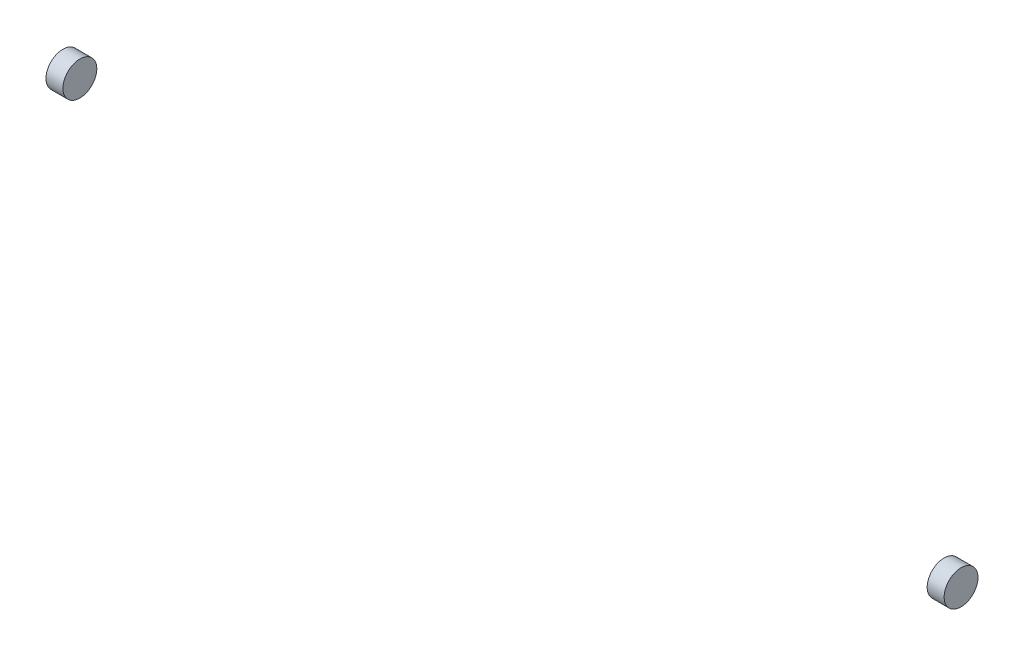
SolidWorks part; units mm, degrees
ref_plane "Front Plane" through (0, 0, 0) normal (0, 0, 1) x (1, 0, 0)
ref_plane "Top Plane" through (0, 0, 0) normal (0, 1, 0) x (1, 0, 0)
ref_plane "Right Plane" through (0, 0, 0) normal (1, 0, 0) x (0, 0, -1)
sketch "Sketch1" plane through (0, 0, 0) normal (1, 0, 0) x (0, 0, -1)
  circle A0 centre (0, -80) radius 120
extrude "Boss-Extrude1" add sketch "Sketch1" along normal blind 120 from offset 3180
sketch "Sketch2" plane through (0, 0, 0) normal (1, 0, 0) x (0, 0, -1)
  circle A0 centre (0, -80) radius 120
extrude "Boss-Extrude2" add sketch "Sketch2" along normal blind 120 from offset 3060
